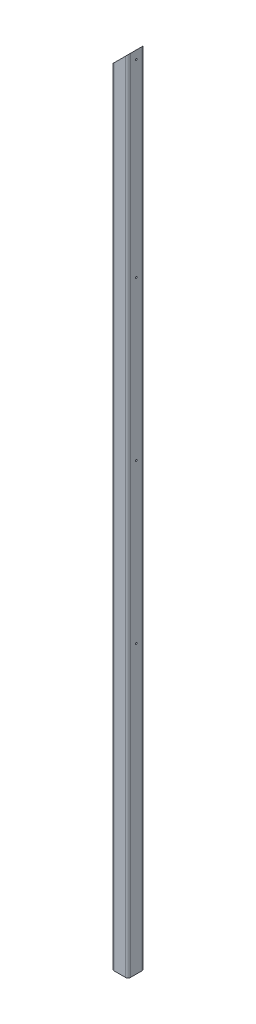
SolidWorks part; units mm, degrees
ref_plane "Front Plane" through (0, 0, 0) normal (0, 0, 1) x (1, 0, 0)
ref_plane "Top Plane" through (0, 0, 0) normal (0, 1, 0) x (1, 0, 0)
ref_plane "Right Plane" through (0, 0, 0) normal (1, 0, 0) x (0, 0, -1)
sketch "Sketch1" plane through (0, 0, 0) normal (0, 0, 1) x (1, 0, 0)
  line L0 (0, 0) -> (0, 1920)
  dimension "D1" = 1920
other "Tube (square) 40 X 40 X 3.2(1)"
ref_plane "Plane1" through (0, 0, 0) normal (0, 1, 0) x (-1, 0, 0)
sketch "Sketch15" plane through (0, 0, 0) normal (0, 1, 0) x (-1, 0, 0)
  line L0 (-13.6, -16.8) -> (13.6, -16.8)
  line L1 (-16.8, -13.6) -> (-16.8, 13.6)
  line L2 (13.6, 16.8) -> (-13.6, 16.8)
  line L3 (16.8, 13.6) -> (16.8, -13.6)
  line L4 (-13.6, -20) -> (13.6, -20)
  line L5 (-20, -13.6) -> (-20, 13.6)
  line L6 (13.6, 20) -> (-13.6, 20)
  line L7 (20, 13.6) -> (20, -13.6)
  line L8 (-20, 0) -> (-16.8, 0) construction
  line L9 (-16.8, 0) -> (16.8, 0) construction
  line L10 (16.8, 0) -> (20, 0) construction
  line L12 (0, 20) -> (0, 16.8) construction
  line L13 (0, 16.8) -> (0, -16.8) construction
  line L14 (0, -16.8) -> (0, -20) construction
  arc A0 (20, 13.6) -> (13.6, 20) centre (13.6, 13.6) ccw
  arc A1 (13.6, -20) -> (20, -13.6) centre (13.6, -13.6) ccw
  arc A2 (-20, -13.6) -> (-13.6, -20) centre (-13.6, -13.6) ccw
  arc A3 (-13.6, 20) -> (-20, 13.6) centre (-13.6, 13.6) ccw
  arc A4 (-13.6, 16.8) -> (-16.8, 13.6) centre (-13.6, 13.6) ccw
  arc A5 (16.8, 13.6) -> (13.6, 16.8) centre (13.6, 13.6) ccw
  arc A6 (13.6, -16.8) -> (16.8, -13.6) centre (13.6, -13.6) ccw
  arc A7 (-16.8, -13.6) -> (-13.6, -16.8) centre (-13.6, -13.6) ccw
  point P2 (-20, 20)
  point P33 (-20, -20)
  point P34 (20, -20)
  point P36 (20, 20)
  point P37 (0, 0)
  dimension "D1" = 6.4
  dimension "Thickness" = 3.2
  dimension "V_leg" = 40
  dimension "H_leg" = 40
ref_plane "Plane2" through (0, 0, -20) normal (0, 0, -1) x (-1, 0, 0)
sketch "Sketch13" plane through (0, 0, -20) normal (0, 0, -1) x (-1, 0, 0)
  line L2 (20, 1920) -> (20, 0) construction
  line L3 (20, 1920) -> (20, 1880)
  line L4 (-13.6, 1920) -> (13.6, 1920) construction
  line L5 (-20, 1920) -> (20, 1920)
  line L9 (20, 1880) -> (-20, 1920)
  line L10 (20, 1920) -> (20, 1880)
  dimension "D1" = 40
extrude "Cut-Extrude1" cut sketch "Sketch13" against normal through all contours L9 L3 L5
ref_plane "Plane3" through (20, 0, 0) normal (1, 0, 0) x (0, 0, -1)
sketch "Sketch16" plane through (20, 0, 0) normal (1, 0, 0) x (0, 0, -1)
  line L0 (-13.6, 1920) -> (13.6, 1920) construction
  line L1 (-13.6, 1920) -> (13.6, 1920) construction
  line L2 (-13.6, 1900) -> (13.6, 1900) construction
  line L3 (-13.6, 1447) -> (13.6, 1447) construction
  line L4 (-13.6, 1067) -> (13.6, 1067) construction
  line L5 (-13.6, 687) -> (13.6, 687) construction
  circle A0 centre (0, 1900) radius 2
  circle A1 centre (0, 1447) radius 2
  circle A2 centre (0, 1067) radius 2
  circle A3 centre (0, 687) radius 2
  dimension "D4" = 4
  dimension "D5" = 1233
  dimension "D1" = 20
  dimension "D2" = 453
  dimension "D3" = 833
extrude "Cut-Extrude2" cut sketch "Sketch16" against normal blind 3
